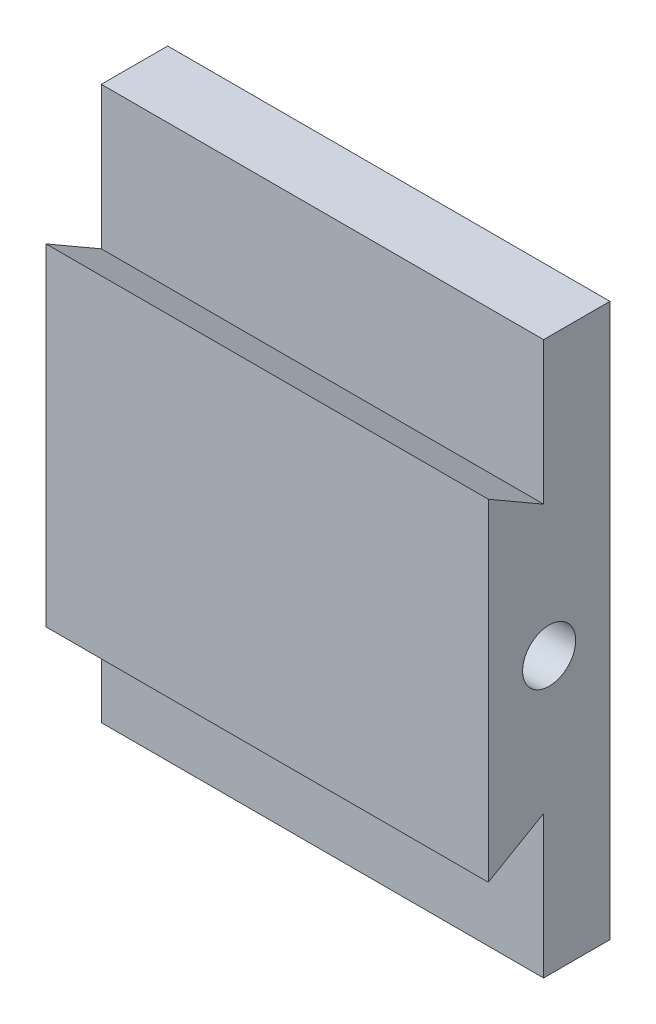
SolidWorks part; units mm, degrees
material "Polyetheretherketone (PEEK)"
ref_plane "Front Plane" through (0, 0, 0) normal (0, 0, 1) x (1, 0, 0)
ref_plane "Top Plane" through (0, 0, 0) normal (0, 1, 0) x (1, 0, 0)
ref_plane "Right Plane" through (0, 0, 0) normal (1, 0, 0) x (0, 0, -1)
sketch "Sketch1" plane through (0, 0, 0) normal (1, 0, 0) x (0, 0, -1)
  line L0 (0, -1.5) -> (0, 1.5)
  line L1 (0, 1.5) -> (0.5, 1.2113)
  line L2 (0.5, 1.2113) -> (0.5, 2.5)
  line L3 (0.5, 2.5) -> (1.1, 2.5)
  line L4 (1.1, 2.5) -> (1.1, -2.5)
  line L5 (1.1, -2.5) -> (0.5, -2.5)
  line L6 (0.5, -2.5) -> (0.5, -1.2113)
  line L7 (0.5, -1.2113) -> (0, -1.5)
  point P4 (0, 0)
  point P12 (1.1, 0)
  dimension "D1" = 3
  dimension "D2" = 60
  dimension "D3" = 60
  dimension "D4" = 5
  dimension "D5" = 0.6
  dimension "D6" = 0.5
  dimension "D7" = 0.5
extrude "Boss-Extrude1" add sketch "Sketch1" along normal blind 4
sketch "Sketch2" plane through (4, 0, 0) normal (1, 0, 0) x (0, 0, -1)
  circle A0 centre (0.55, 0) radius 0.24
  dimension "D1" = 0.48
  dimension "D2" = 0.55
extrude "Cut-Extrude1" cut sketch "Sketch2" against normal through all
